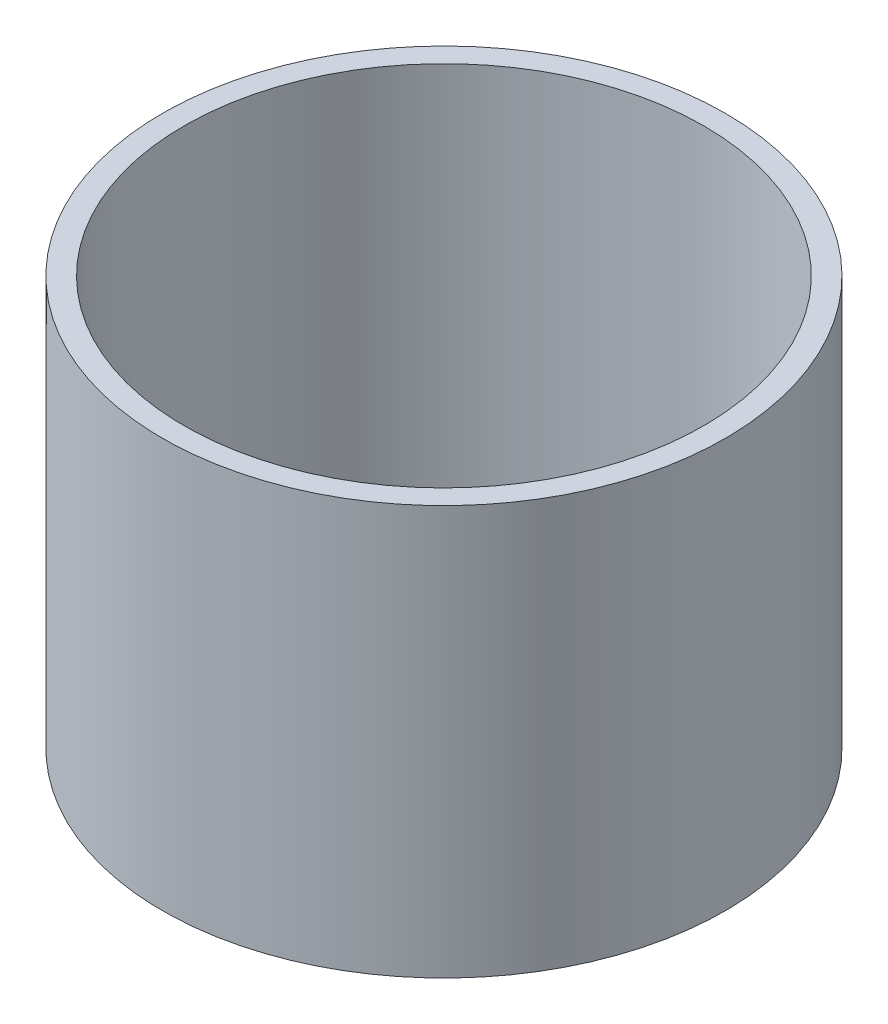
SolidWorks part; units mm, degrees
ref_plane "Front Plane" through (0, 0, 0) normal (0, 0, 1) x (1, 0, 0)
ref_plane "Top Plane" through (0, 0, 0) normal (0, 1, 0) x (1, 0, 0)
ref_plane "Right Plane" through (0, 0, 0) normal (1, 0, 0) x (0, 0, -1)
sketch "Sketch1" plane through (0, 0, 0) normal (0, 1, 0) x (1, 0, 0)
  circle A0 centre (0, 0) radius 61.9125
  circle A1 centre (0, 0) radius 57.15
extrude "Boss-Extrude1" add sketch "Sketch1" along normal blind 90
